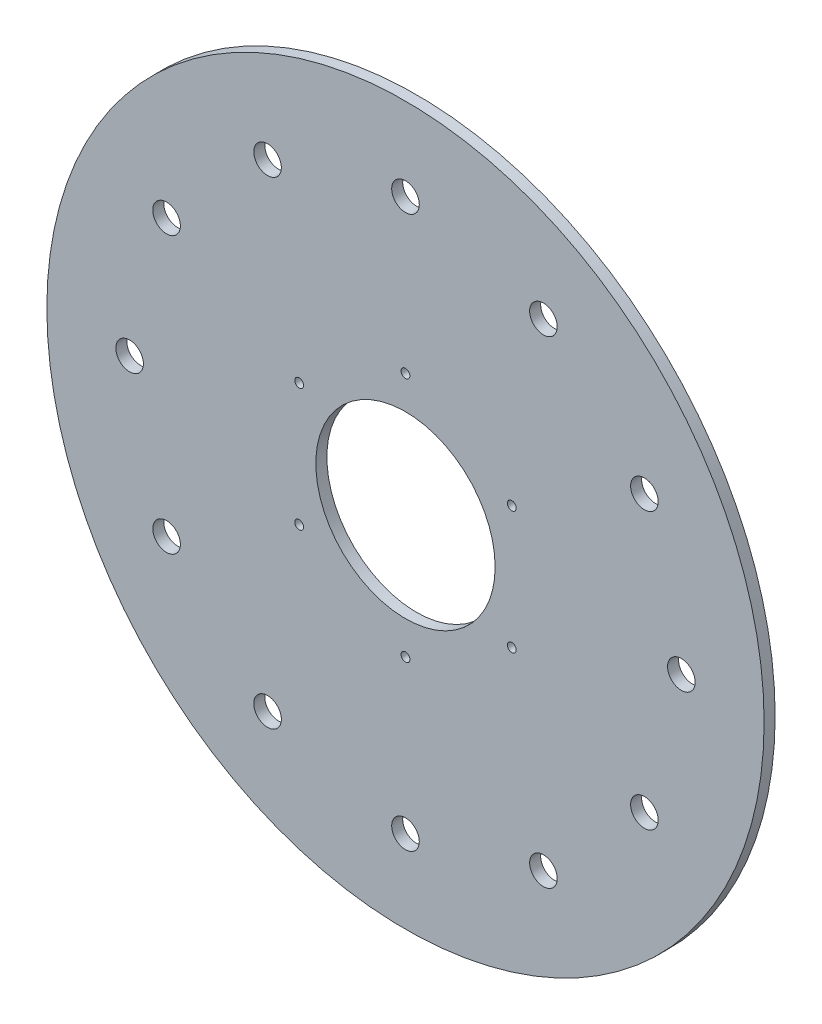
SolidWorks part; units mm, degrees
material "Thornel Mat VMA"
ref_plane "前视基准面" through (0, 0, 0) normal (0, 0, 1) x (1, 0, 0)
ref_plane "上视基准面" through (0, 0, 0) normal (0, 1, 0) x (1, 0, 0)
ref_plane "右视基准面" through (0, 0, 0) normal (1, 0, 0) x (0, 0, -1)
sketch "草图1" plane through (0, 0, 0) normal (0, 0, 1) x (1, 0, 0)
  circle A0 centre (0, 0) radius 130
  circle A1 centre (0, 0) radius 32.5
  circle A2 centre (0, 0) radius 100 construction
  circle A3 centre (0, 100) radius 5
  circle A4 centre (50, 86.6025) radius 5
  circle A5 centre (86.6025, 50) radius 5
  circle A6 centre (100, 0) radius 5
  circle A7 centre (86.6025, -50) radius 5
  circle A8 centre (50, -86.6025) radius 5
  circle A9 centre (0, -100) radius 5
  circle A10 centre (-50, -86.6025) radius 5
  circle A11 centre (-86.6025, -50) radius 5
  circle A12 centre (-100, 0) radius 5
  circle A13 centre (-86.6025, 50) radius 5
  circle A14 centre (-50, 86.6025) radius 5
  circle A15 centre (0, 0) radius 44.5 construction
  circle A16 centre (0, 44.5) radius 1.6
  circle A17 centre (38.5381, 22.25) radius 1.6
  circle A18 centre (38.5381, -22.25) radius 1.6
  circle A19 centre (0, -44.5) radius 1.6
  circle A20 centre (-38.5381, -22.25) radius 1.6
  circle A21 centre (-38.5381, 22.25) radius 1.6
  point P32 (0, 0)
  point P46 (0, 0)
  dimension "D1" = 260
  dimension "D2" = 65
  dimension "D3" = 200
  dimension "D4" = 10
  dimension "D6" = 89
  dimension "D7" = 3.2
  dimension "D5" = 12
  dimension "D8" = 6
extrude "凸台-拉伸1" add sketch "草图1" along normal blind 4
